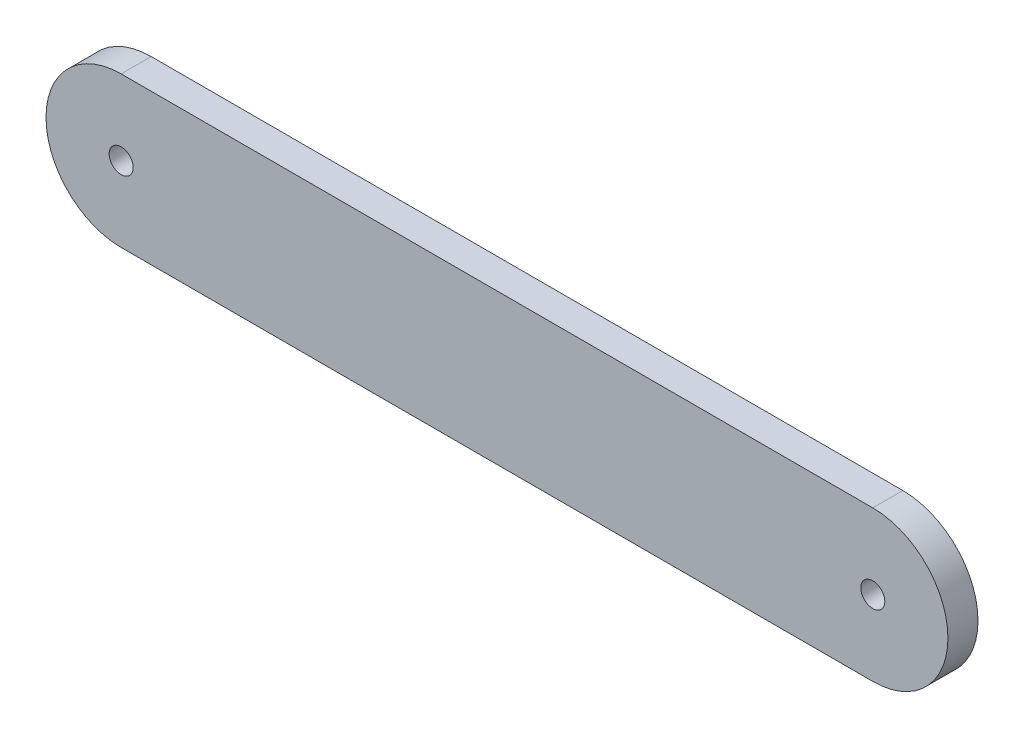
SolidWorks part; units mm, degrees
material "ABS"
ref_plane "正面" through (0, 0, 0) normal (0, 0, 1) x (1, 0, 0)
ref_plane "平面" through (0, 0, 0) normal (0, 1, 0) x (1, 0, 0)
ref_plane "右側面" through (0, 0, 0) normal (1, 0, 0) x (0, 0, -1)
sketch "ｽｹｯﾁ1" plane through (0, 0, 0) normal (0, 0, 1) x (1, 0, 0)
  line L0 (0, 0) -> (100, 0) construction
  line L1 (0, 10) -> (100, 10)
  line L2 (0, -10) -> (100, -10)
  arc A0 (0, 10) -> (0, -10) centre (0, 0) ccw
  arc A1 (100, -10) -> (100, 10) centre (100, 0) ccw
  circle A2 centre (0, 0) radius 1.6
  circle A3 centre (100, 0) radius 1.6
  point P3 (50, 0)
  dimension "D1" = 10
  dimension "D2" = 3.2
  dimension "D3" = 100
extrude "ﾎﾞｽ - 押し出し1" add sketch "ｽｹｯﾁ1" along normal blind 4
